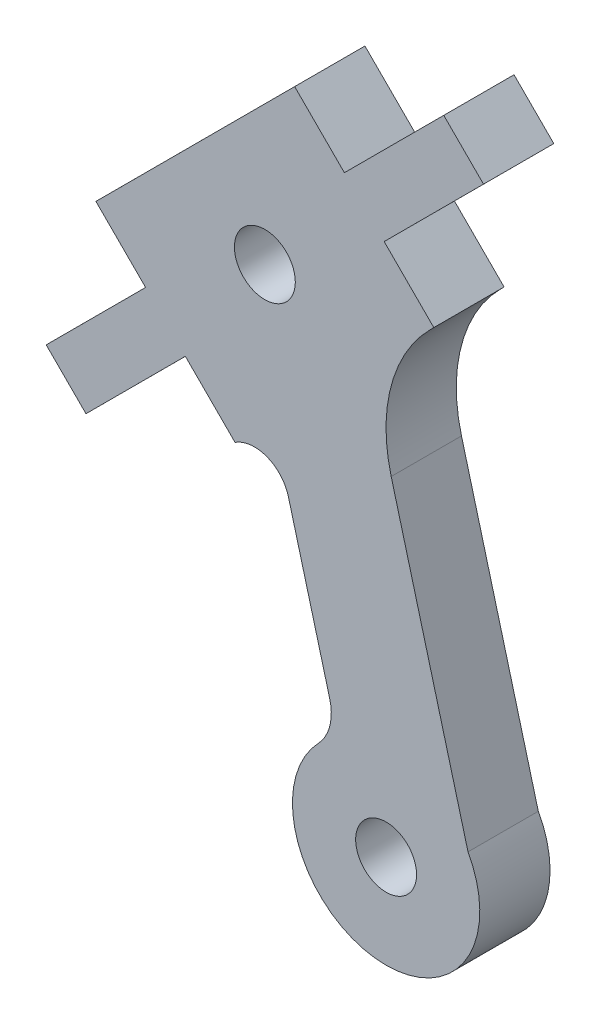
SolidWorks part; units mm, degrees
ref_plane "前视基准面" through (0, 0, 0) normal (0, 0, 1) x (1, 0, 0)
ref_plane "上视基准面" through (0, 0, 0) normal (0, 1, 0) x (1, 0, 0)
ref_plane "右视基准面" through (0, 0, 0) normal (1, 0, 0) x (0, 0, -1)
ref_plane "基准面4" through (0, 0, -3.3629) normal (0, 0, -1) x (-1, 0, 0)
sketch "草图1" plane through (0, 0, -3.3629) normal (0, 0, -1) x (-1, 0, 0)
  line L0 (-8.9295, 17.4533) -> (-12.2085, 5.2163)
  line L1 (-6.3042, 7.9338) -> (-4.5397, 14.5186)
  line L2 (-2.2643, 15.3821) -> (-0.1425, 17.5032)
  line L3 (-0.1425, 17.5032) -> (4.0998, 13.2597)
  line L4 (4.0998, 13.2597) -> (5.7975, 14.9569)
  line L5 (5.7975, 14.9569) -> (1.5545, 19.201)
  line L6 (1.5545, 19.201) -> (3.6758, 21.3217)
  line L7 (3.6758, 21.3217) -> (-4.8084, 29.8083)
  line L8 (-4.8084, 29.8083) -> (-6.932, 27.6854)
  line L9 (-6.932, 27.6854) -> (-11.1732, 31.9279)
  line L10 (-11.1732, 31.9279) -> (-12.8704, 30.2312)
  line L11 (-12.8704, 30.2312) -> (-8.6291, 25.9887)
  line L12 (-8.6291, 25.9887) -> (-10.7491, 23.8693)
  line L13 (-10.7491, 23.8693) -> (-10.6111, 23.7313)
  circle A0 centre (-3.5366, 22.594) radius 1.3
  arc A1 (-10.6111, 23.7313) -> (-8.9295, 17.4533) centre (-15.208, 19.1357) cw
  arc A2 (-12.2085, 5.2163) -> (-5.8193, 6.0355) centre (-8.7125, 3.275) ccw
  arc A3 (-5.8193, 6.0355) -> (-6.3042, 7.9338) centre (-4.3723, 7.4162) cw
  arc A4 (-4.5397, 14.5186) -> (-2.2643, 15.3821) centre (-3.0908, 14.1303) cw
  circle A5 centre (-8.7125, 3.275) radius 1.3
extrude "凸台-拉伸1" add sketch "草图1" against normal blind 3
